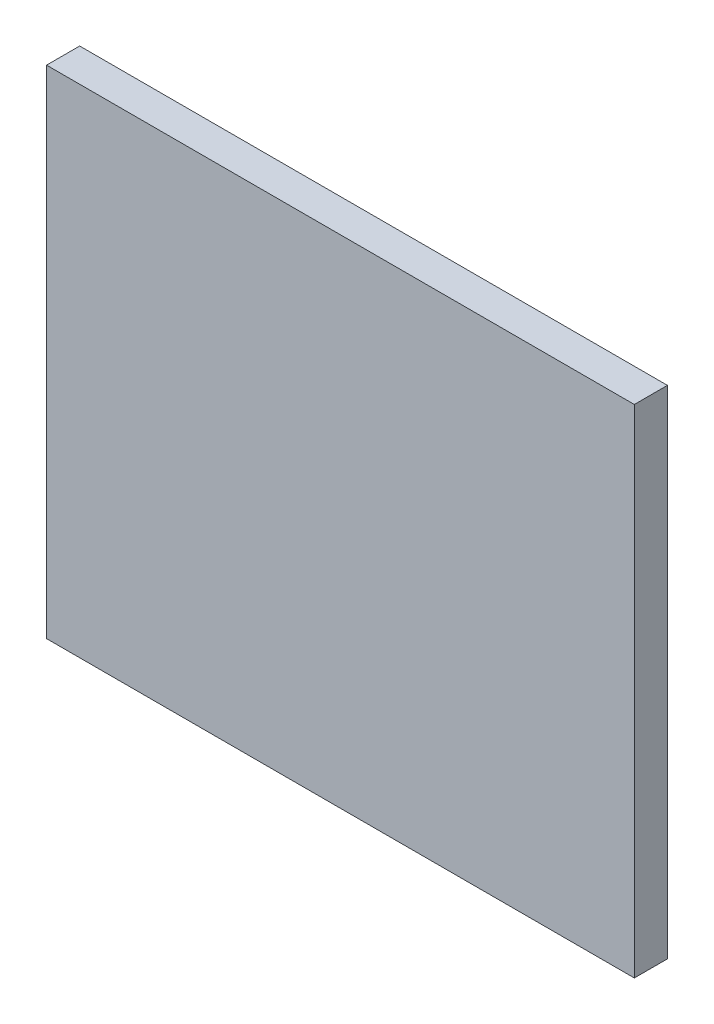
SolidWorks part; units mm, degrees
ref_plane "Front Plane" through (0, 0, 0) normal (0, 0, 1) x (1, 0, 0)
ref_plane "Top Plane" through (0, 0, 0) normal (0, 1, 0) x (1, 0, 0)
ref_plane "Right Plane" through (0, 0, 0) normal (1, 0, 0) x (0, 0, -1)
sketch "Sketch1" plane through (0, 0, 0) normal (0, 1, 0) x (1, 0, 0)
  line L1 (0, 0) -> (71, 0)
  line L2 (0, 0) -> (0, 4)
  line L3 (0, 4) -> (71, 4)
  line L4 (71, 0) -> (71, 4)
  dimension "D1" = 71
  dimension "D2" = 4
extrude "Boss-Extrude1" add sketch "Sketch1" along normal blind 60
